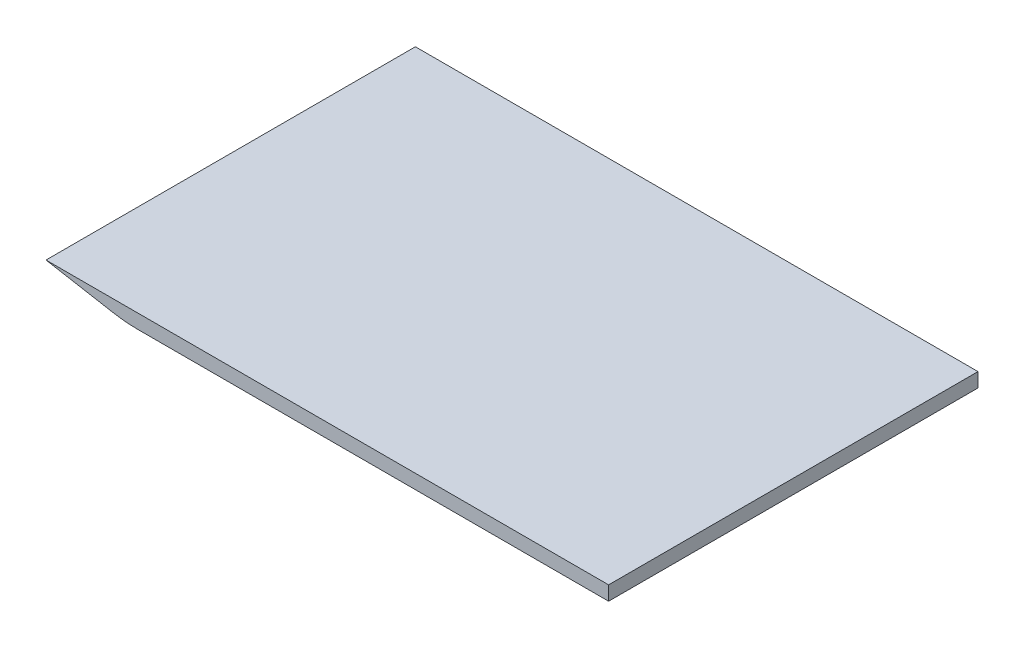
SolidWorks part; units mm, degrees
ref_plane "Front Plane" through (0, 0, 0) normal (0, 0, 1) x (1, 0, 0)
ref_plane "Top Plane" through (0, 0, 0) normal (0, 1, 0) x (1, 0, 0)
ref_plane "Right Plane" through (0, 0, 0) normal (1, 0, 0) x (0, 0, -1)
sketch "Sketch1" plane through (0, 0, 0) normal (0, 0, 1) x (1, 0, 0)
  line L0 (0, 0) -> (198, 0)
  line L1 (198, 0) -> (198, -5)
  line L2 (198, -5) -> (28, -5)
  line L3 (28, -5) -> (0, 0)
  dimension "D1" = 5
  dimension "D2" = 170
  dimension "D3" = 28
extrude "Boss-Extrude1" add sketch "Sketch1" along normal blind 130 contours L3 L0 L1 L2
fillet "Fillet1" radius 50 1 edges at (28, -5, 65)
